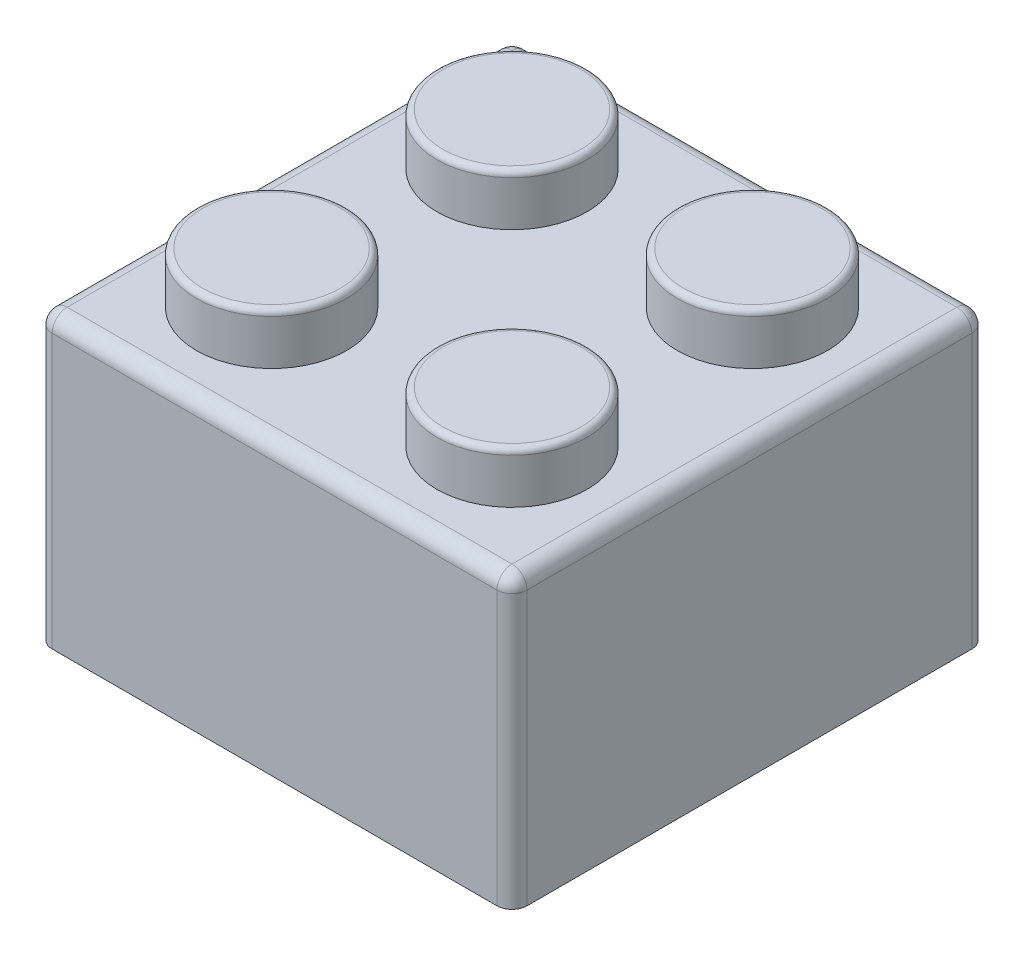
SolidWorks part; units mm, degrees
ref_plane "Front Plane" through (0, 0, 0) normal (0, 0, 1) x (1, 0, 0)
ref_plane "Top Plane" through (0, 0, 0) normal (0, 1, 0) x (1, 0, 0)
ref_plane "Right Plane" through (0, 0, 0) normal (1, 0, 0) x (0, 0, -1)
sketch "Sketch1" plane through (0, 0, 0) normal (0, 1, 0) x (1, 0, 0)
  line L1 (-7.5254, 6.572) -> (8.2746, 6.572)
  line L2 (-7.5254, 6.572) -> (-7.5254, -9.228)
  line L3 (-7.5254, -9.228) -> (8.2746, -9.228)
  line L4 (8.2746, 6.572) -> (8.2746, -9.228)
  dimension "D1" = 15.8
  dimension "D2" = 15.8
extrude "Boss-Extrude1" add sketch "Sketch1" along normal blind 9.6
fillet "Fillet1" radius 0.5 8 edges at (8.2746, 4.8, -6.572) (-7.5254, 4.8, -6.572) (8.2746, 4.8, 9.228) (8.2746, 9.6, 1.328) (0.3746, 9.6, -6.572) (-7.5254, 9.6, 1.328) (0.3746, 9.6, 9.228) (-7.5254, 4.8, 9.228)
sketch "Sketch2" plane through (0, 0, 0) normal (0, -1, 0) x (1, 0, 0)
  line L0 (7.7746, -6.572) -> (-7.0254, -6.572) construction
  line L1 (6.7846, 7.738) -> (-6.0354, 7.738)
  line L2 (6.7846, 7.738) -> (6.7846, -5.082)
  line L3 (6.7846, -5.082) -> (-6.0354, -5.082)
  line L4 (-6.0354, 7.738) -> (-6.0354, -5.082)
  line L5 (-7.0254, 9.228) -> (7.7746, 9.228) construction
  line L6 (8.2746, 8.728) -> (8.2746, -6.072) construction
  line L7 (-7.5254, -6.072) -> (-7.5254, 8.728) construction
  dimension "D1" = 1.49
  dimension "D2" = 1.49
  dimension "D3" = 1.49
  dimension "D4" = 1.49
extrude "Cut-Extrude1" cut sketch "Sketch2" against normal blind 8.1
sketch "Sketch3" plane through (0, 9.6, 0) normal (0, 1, 0) x (1, 0, 0)
  line L0 (-7.0254, 6.572) -> (7.7746, 6.572) construction
  line L2 (-7.5254, -8.728) -> (-7.5254, 6.072) construction
  circle A0 centre (-3.6254, 2.672) radius 2.5
  point P6 (-17.1478, -0.0514)
  dimension "D1" = 3.9
  dimension "D2" = 3.9
extrude "Boss-Extrude2" add sketch "Sketch3" along normal blind 1.7
fillet "Fillet2" radius 0.2 1 edges at (-3.6254, 11.3, -0.172)
pattern_linear "LPattern1" count 2 spacing 8 along (1, 0, 0) count 2 spacing 8 along (0, 0, 1) of "Boss-Extrude2", "Fillet2"
sketch "Sketch4" plane through (0, 8.1, 0) normal (0, -1, 0) x (1, 0, 0)
  line L0 (8.2746, 8.728) -> (8.2746, -6.072) construction
  line L1 (-7.0254, 9.228) -> (7.7746, 9.228) construction
  circle A0 centre (0.3746, 1.328) radius 3.155
  point P6 (0.3746, 9.228)
  dimension "D1" = 7.9
  dimension "D2" = 7.9
extrude "Boss-Extrude3" add sketch "Sketch4" along normal blind 8.1
sketch "Sketch5" plane through (0, 0, 0) normal (0, -1, 0) x (1, 0, 0)
  circle A0 centre (0.3746, 1.328) radius 2.655
  circle A1 centre (0.3746, 1.328) radius 3.155 construction
  dimension "D1" = 0.5
extrude "Cut-Extrude2" cut sketch "Sketch5" against normal blind 8.1
